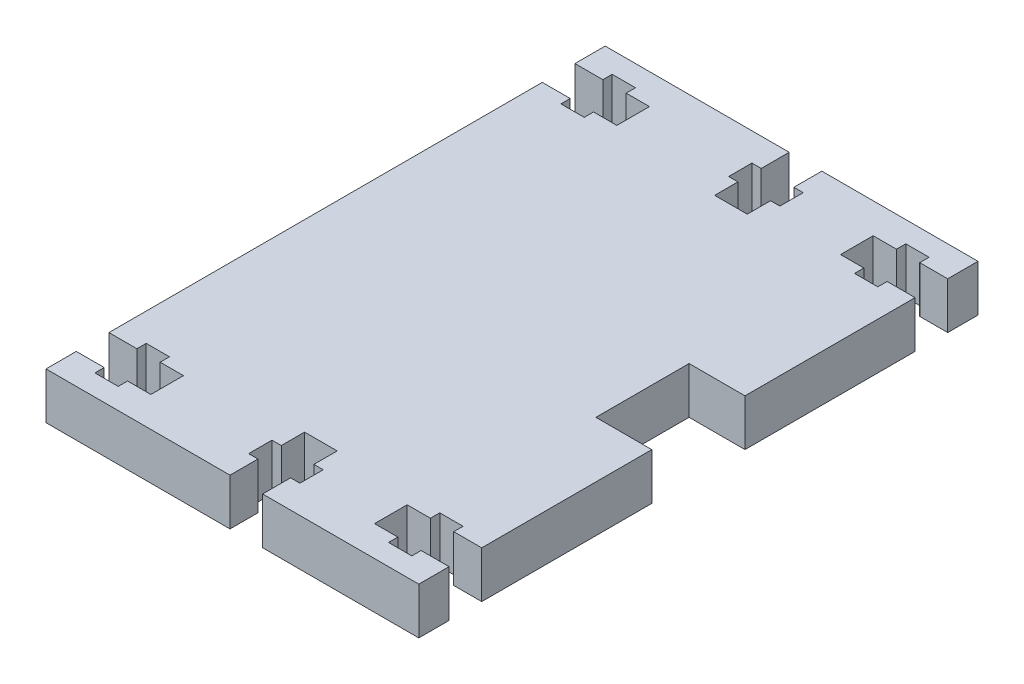
SolidWorks part; units mm, degrees
ref_plane "Front Plane" through (0, 0, 0) normal (0, 0, 1) x (1, 0, 0)
ref_plane "Top Plane" through (0, 0, 0) normal (0, 1, 0) x (1, 0, 0)
ref_plane "Right Plane" through (0, 0, 0) normal (1, 0, 0) x (0, 0, -1)
sketch "草图1" plane through (0, 0, 0) normal (0, 1, 0) x (1, 0, 0)
  line L0 (0.2567, -175.6236) -> (0.2567, 163.4105) construction
  line L1 (-88.6979, 0) -> (96.047, 0) construction
  line L2 (-19.7433, 26.75) -> (-16.7433, 26.75)
  line L3 (20.2567, -30) -> (-19.7433, -30)
  line L4 (20.2567, -30) -> (20.2567, 30)
  line L5 (20.2567, 30) -> (-19.7433, 30)
  line L6 (-19.7433, -30) -> (-19.7433, 30)
  line L7 (12.2567, 26.75) -> (12.2567, 23.25)
  line L8 (14.7567, 23.25) -> (14.7567, 22.25)
  line L9 (-16.7433, 26.75) -> (-16.7433, 27.75)
  line L10 (-16.7433, 27.75) -> (-14.2433, 27.75)
  line L11 (-14.2433, 27.75) -> (-14.2433, 26.75)
  line L12 (-14.2433, 26.75) -> (-11.7433, 26.75)
  line L13 (-11.7433, 26.75) -> (-11.7433, 23.25)
  line L14 (-11.7433, 23.25) -> (-14.2433, 23.25)
  line L15 (-14.2433, 23.25) -> (-14.2433, 22.25)
  line L16 (-14.2433, 22.25) -> (-16.7433, 22.25)
  line L17 (-16.7433, 22.25) -> (-16.7433, 23.25)
  line L18 (-16.7433, 23.25) -> (-19.7433, 23.25)
  line L19 (17.2567, 23.25) -> (20.2567, 23.25)
  line L20 (17.2567, 22.25) -> (17.2567, 23.25)
  line L21 (14.7567, 22.25) -> (17.2567, 22.25)
  line L22 (12.2567, 23.25) -> (14.7567, 23.25)
  line L23 (20.2567, -30) -> (20.2567, 30)
  line L24 (-19.7433, -30) -> (-19.7433, 30)
  line L25 (14.7567, 26.75) -> (12.2567, 26.75)
  line L26 (14.7567, 27.75) -> (14.7567, 26.75)
  line L27 (17.2567, 27.75) -> (14.7567, 27.75)
  line L28 (17.2567, 26.75) -> (17.2567, 27.75)
  line L29 (20.2567, 26.75) -> (17.2567, 26.75)
  line L30 (14.7567, -27.75) -> (14.7567, -26.75)
  line L31 (17.2567, -22.25) -> (17.2567, -23.25)
  line L32 (14.7567, -23.25) -> (14.7567, -22.25)
  line L33 (14.7567, -22.25) -> (17.2567, -22.25)
  line L34 (17.2567, -26.75) -> (17.2567, -27.75)
  line L35 (17.2567, -23.25) -> (20.2567, -23.25)
  line L36 (20.2567, -26.75) -> (17.2567, -26.75)
  line L37 (17.2567, -27.75) -> (14.7567, -27.75)
  line L38 (14.7567, -26.75) -> (12.2567, -26.75)
  line L39 (12.2567, -26.75) -> (12.2567, -23.25)
  line L40 (12.2567, -23.25) -> (14.7567, -23.25)
  line L41 (-19.7433, -26.75) -> (-16.7433, -26.75)
  line L42 (-16.7433, -26.75) -> (-16.7433, -27.75)
  line L43 (-16.7433, -27.75) -> (-14.2433, -27.75)
  line L44 (-14.2433, -27.75) -> (-14.2433, -26.75)
  line L45 (-14.2433, -26.75) -> (-11.7433, -26.75)
  line L46 (-11.7433, -26.75) -> (-11.7433, -23.25)
  line L47 (-16.7433, -22.25) -> (-16.7433, -23.25)
  line L48 (-14.2433, -23.25) -> (-14.2433, -22.25)
  line L49 (-11.7433, -23.25) -> (-14.2433, -23.25)
  line L50 (-14.2433, -22.25) -> (-16.7433, -22.25)
  line L51 (-16.7433, -23.25) -> (-19.7433, -23.25)
  line L53 (20.2567, -5) -> (14.2567, -5)
  line L54 (20.2567, -5) -> (20.2567, 5)
  line L55 (20.2567, 5) -> (14.2567, 5)
  line L56 (14.2567, -5) -> (14.2567, 5)
  line L57 (20.2567, -5) -> (14.2567, 5) construction
  line L58 (20.2567, 5) -> (14.2567, -5) construction
  point P5 (0, 0)
  point P58 (17.2567, 0)
  dimension "D1" = 60
  dimension "D2" = 20
  dimension "D3" = 2.5
  dimension "D4" = 2.5
  dimension "D5" = 5.5
  dimension "D6" = 3.5
  dimension "D7" = 3.5
  dimension "D8" = 1
  dimension "D9" = 3.25
  dimension "D10" = 1
  dimension "D11" = 8
  dimension "D12" = 3
  dimension "D13" = 30
  dimension "D14" = 10
  dimension "D15" = 6
  dimension "D16" = 6
extrude "凸台-拉伸1" add sketch "草图1" along normal blind 5 contours L51 L47 L50 L48 L49 L46 L45 L44 L43 L42 L41 L6 L3 L4 L36 L34 L37 L30 L38 L39 L40 L32 L33 L31 L35 L23 L19 L20 L21 L8 L22 L7 L25 L26 L27 L28 L29 L5 L2 L9 L10 L11 L12 L13 L14 L15 L16 L17 L18
sketch "草图2" plane through (0, 5, 0) normal (0, 1, 0) x (1, 0, 0)
  line L0 (1.75, 39.2316) -> (1.75, -47.4985) construction
  line L1 (0, 30) -> (0, 27)
  line L2 (20.2567, 30) -> (-19.7433, 30) construction
  line L3 (0, 27) -> (-1, 27)
  line L4 (-1, 27) -> (-1, 24.5)
  line L5 (-1, 24.5) -> (0, 24.5)
  line L6 (0, 24.5) -> (0, 22)
  line L7 (0, 22) -> (3.5, 22)
  line L8 (3.5, 22) -> (3.5, 24.5)
  line L9 (3.5, 24.5) -> (4.5, 24.5)
  line L10 (4.5, 24.5) -> (4.5, 27)
  line L11 (4.5, 27) -> (3.5, 27)
  line L12 (3.5, 27) -> (3.5, 30)
  line L13 (3.5, 30) -> (0, 30)
  line L18 (-30.1375, 0) -> (28.5791, 0) construction
  line L19 (3.5, -30) -> (0, -30)
  line L20 (-1, -24.5) -> (0, -24.5)
  line L21 (-1, -27) -> (-1, -24.5)
  line L22 (0, -27) -> (-1, -27)
  line L23 (0, -30) -> (0, -27)
  line L24 (4.5, -27) -> (3.5, -27)
  line L25 (3.5, -27) -> (3.5, -30)
  line L26 (4.5, -24.5) -> (4.5, -27)
  line L27 (3.5, -24.5) -> (4.5, -24.5)
  line L28 (3.5, -22) -> (3.5, -24.5)
  line L29 (0, -22) -> (3.5, -22)
  line L30 (0, -24.5) -> (0, -22)
  dimension "D1" = 3
  dimension "D2" = 2.5
  dimension "D3" = 8
  dimension "D4" = 3
  dimension "D5" = 2.5
  dimension "D6" = 3.5
  dimension "D7" = 1.75
  dimension "D8" = 2.75
  dimension "D9" = 5.5
  dimension "D10" = 1.75
extrude "切除-拉伸1" cut sketch "草图2" against normal blind 5
